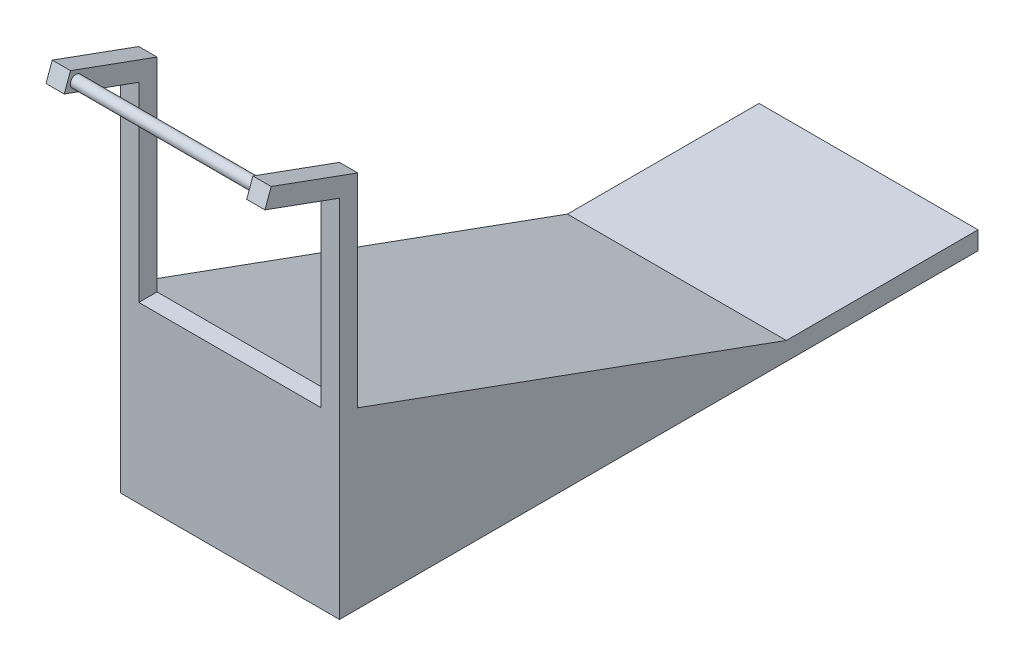
SolidWorks part; units mm, degrees
other "Markup1"
sketch "Sketch7" plane through (0, 44.8547, 8.1745) normal (-0.9055, 0.148, 0.3977) x (0.4234, 0.2514, 0.8704)
ref_plane "Front Plane" through (0, 0, 0) normal (0, 0, 1) x (1, 0, 0)
ref_plane "Top Plane" through (0, 0, 0) normal (0, 1, 0) x (1, 0, 0)
ref_plane "Right Plane" through (0, 0, 0) normal (1, 0, 0) x (0, 0, -1)
sketch "Sketch2" plane through (0, 0, 0) normal (1, 0, 0) x (0, 0, -1)
  line L0 (0, 0) -> (70, 0)
  line L1 (70, 0) -> (70, 2)
  line L2 (70, 2) -> (48.9846, 2)
  line L3 (48.9846, 2) -> (2, 19.101)
  line L4 (2, 19.101) -> (2, 41.4004)
  line L6 (0, 40) -> (0, 0)
  line L8 (2, 41.4004) -> (-7.4905, 44.8547)
  line L9 (-7.4905, 44.8547) -> (-8.1745, 42.9753)
  line L10 (-8.1745, 42.9753) -> (0, 40)
  dimension "D1" = 70
  dimension "D2" = 2
  dimension "D3" = 2
  dimension "D4" = 70
  dimension "D5" = 20
  dimension "D6" = 2
  dimension "D7" = 40
  dimension "D8" = 50
extrude "Boss-Extrude1" add sketch "Sketch2" along normal blind 24
sketch "Sketch5" plane through (0, 0, -2) normal (0, 0, -1) x (-1, 0, 0)
  line L0 (-24, 19.101) -> (0, 19.101) construction
  line L1 (-22, 19.101) -> (-2, 19.101)
  line L2 (-22, 19.101) -> (-22, 49.2971)
  line L3 (-22, 49.2971) -> (-2, 49.2971)
  line L4 (-2, 19.101) -> (-2, 49.2971)
  line L5 (0, 19.101) -> (0, 41.4004) construction
  line L6 (-24, 19.101) -> (-24, 41.4004) construction
  dimension "D1" = 2
  dimension "D2" = 2
extrude "Cut-Extrude1" cut sketch "Sketch5" against normal blind 20
sketch "Sketch6" plane through (2, 0, 0) normal (1, 0, 0) x (0, 0, -1)
  line L0 (-8.1745, 42.9753) -> (-7.4905, 44.8547) construction
  line L1 (-7.4905, 44.8547) -> (2, 41.4004) construction
  circle A0 centre (-6.8928, 43.573) radius 0.625
  dimension "D3" = 1.25
  dimension "D1" = 1
  dimension "D2" = 1
extrude "Boss-Extrude2" add sketch "Sketch6" along direction (1, 0, 0) on the side of the normal up to next (20 mm away)
